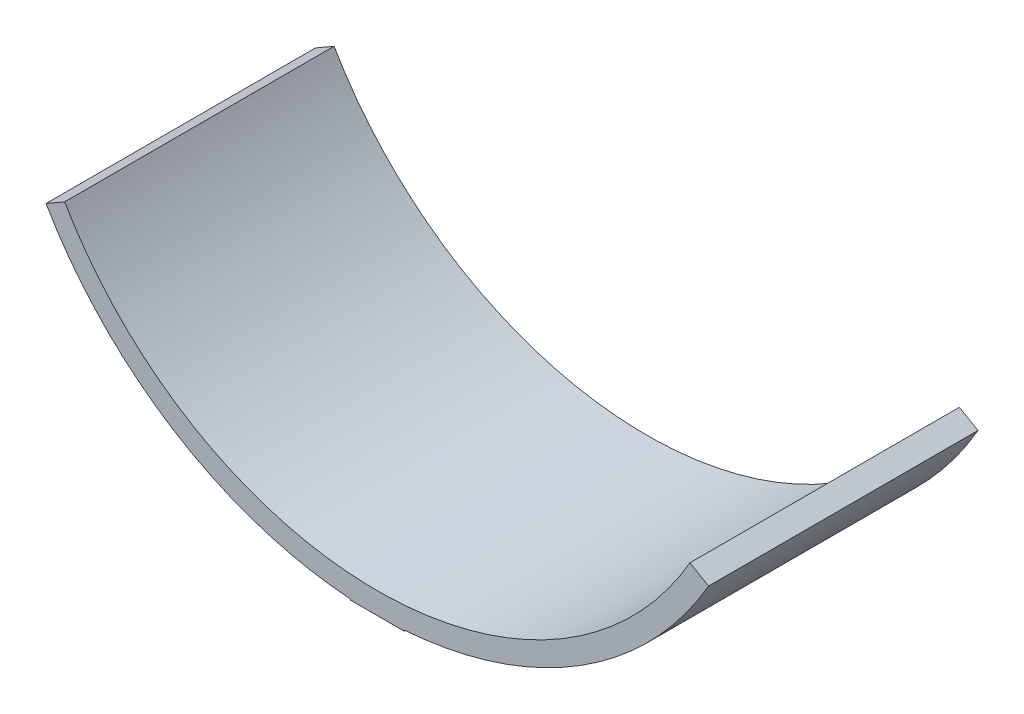
SolidWorks part; units mm, degrees
ref_plane "Front Plane" through (0, 0, 0) normal (0, 0, 1) x (1, 0, 0)
ref_plane "Top Plane" through (0, 0, 0) normal (0, 1, 0) x (1, 0, 0)
ref_plane "Right Plane" through (0, 0, 0) normal (1, 0, 0) x (0, 0, -1)
sketch "Sketch1" plane through (0, 0, 0) normal (0, 0, 1) x (1, 0, 0)
  line L0 (0, -2.54) -> (0, 2.54)
  line L1 (-6.35, -2.54) -> (6.35, -2.54)
  line L2 (-6.35, -2.54) -> (-6.35, 2.54)
  line L3 (-6.35, 2.54) -> (6.35, 2.54)
  line L4 (6.35, -2.54) -> (6.35, 2.54)
  line L5 (-6.35, -2.54) -> (6.35, 2.54) construction
  line L6 (-6.35, 2.54) -> (6.35, -2.54) construction
  line L7 (0, 2.54) -> (0, 129.54) construction
  line L10 (0, 87.63) -> (-97.1594, 31.535) construction
  line L11 (0, 87.63) -> (119.4251, 18.6799) construction
  line L12 (-73.6901, 45.085) -> (-78.0895, 42.545)
  line L13 (78.0895, 42.545) -> (73.6901, 45.085)
  arc A0 (-73.6901, 45.085) -> (73.6901, 45.085) centre (0, 87.63) ccw
  arc A1 (-78.0895, 42.545) -> (78.0895, 42.545) centre (0, 87.63) ccw
  point P0 (0, 0)
  dimension "D2" = 85.09
  dimension "D1" = 5.08
  dimension "0.5" = 12.7
  dimension "D5" = 60
  dimension "D6" = 60
extrude "Boss-Extrude1" add sketch "Sketch1" along normal blind 63.5
